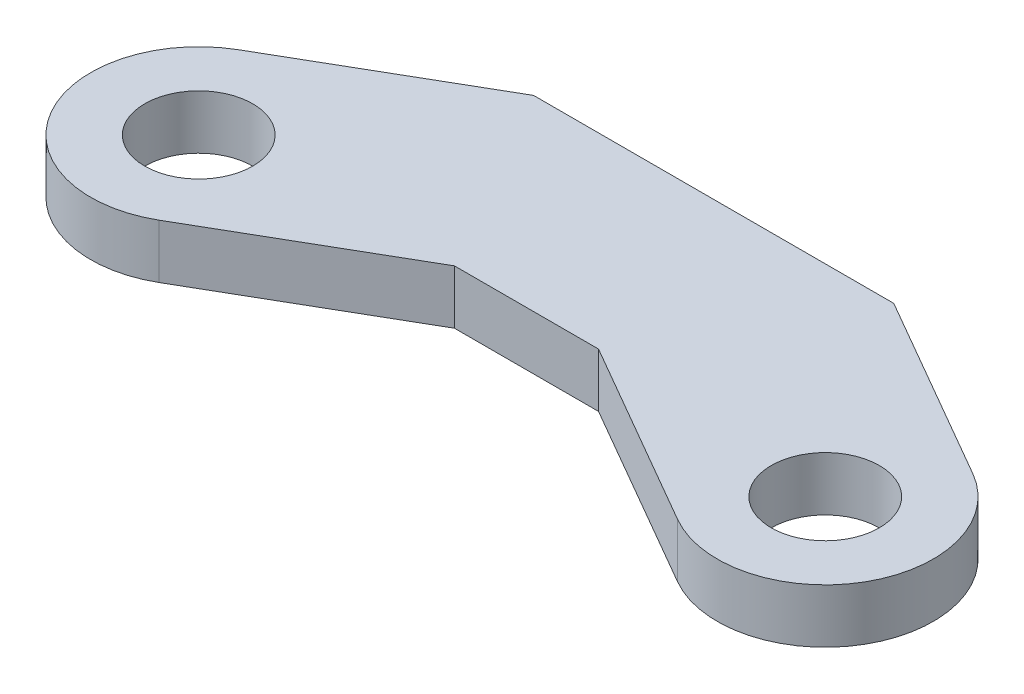
SolidWorks part; units mm, degrees
ref_plane "Front Plane" through (0, 0, 0) normal (0, 0, 1) x (1, 0, 0)
ref_plane "Top Plane" through (0, 0, 0) normal (0, 1, 0) x (1, 0, 0)
ref_plane "Right Plane" through (0, 0, 0) normal (1, 0, 0) x (0, 0, -1)
sketch "Sketch1" plane through (0, 0, 0) normal (0, 1, 0) x (1, 0, 0)
  line L1 (-8.4641, -2) -> (-13.6603, -5)
  line L2 (-5.4641, -7.1962) -> (-10.6603, -10.1962)
  line L10 (-8.4641, -2) -> (1.5359, -2)
  line L11 (-5.4641, -7.1962) -> (-1.4641, -7.1962)
  line L12 (-1.4641, -7.1962) -> (3.7321, -10.1962)
  line L13 (1.5359, -2) -> (6.7321, -5)
  arc A0 (-10.6603, -10.1962) -> (-13.6603, -5) centre (-12.1603, -7.5981) cw
  circle A1 centre (-12.1603, -7.5981) radius 1.5
  circle A4 centre (5.2321, -7.5981) radius 1.5
  arc A5 (3.7321, -10.1962) -> (6.7321, -5) centre (5.2321, -7.5981) ccw
extrude "Boss-Extrude1" add sketch "Sketch1" along normal blind 1.5
